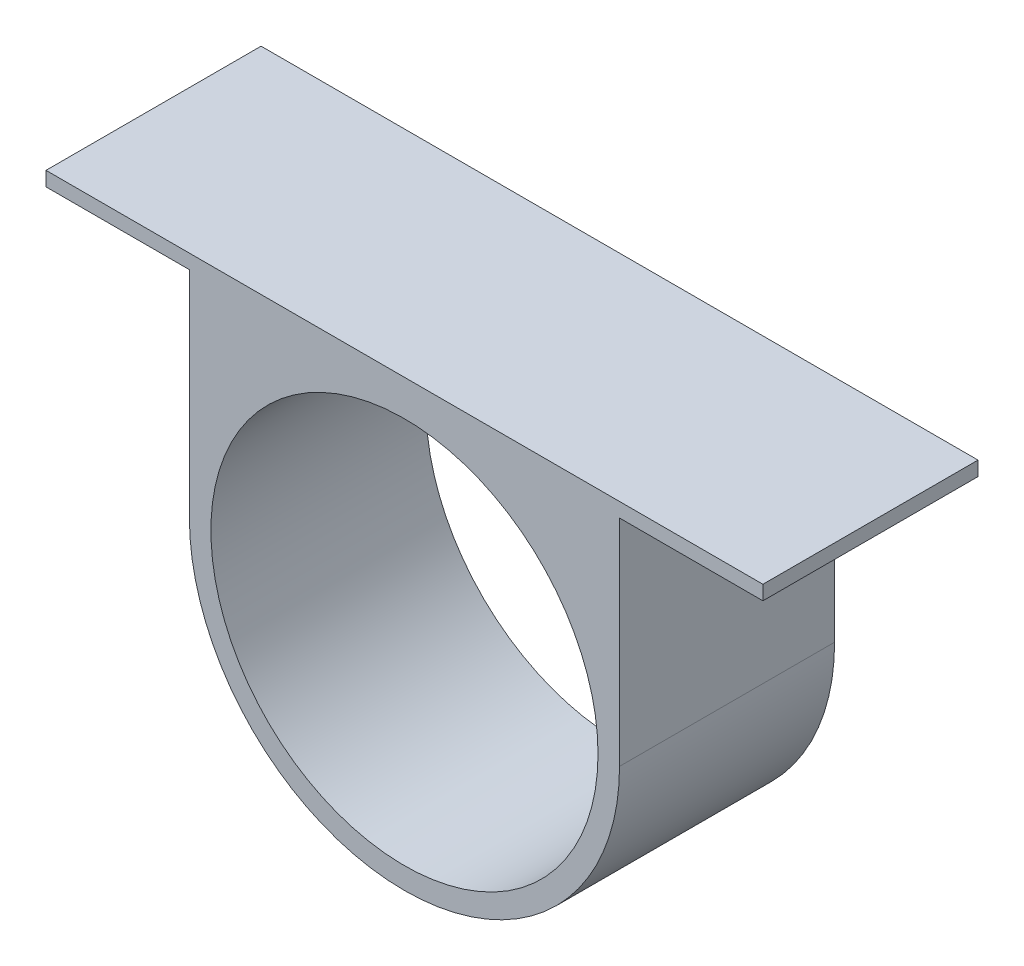
SolidWorks part; units mm, degrees
ref_plane "Front Plane" through (0, 0, 0) normal (0, 0, 1) x (1, 0, 0)
ref_plane "Top Plane" through (0, 0, 0) normal (0, 1, 0) x (1, 0, 0)
ref_plane "Right Plane" through (0, 0, 0) normal (1, 0, 0) x (0, 0, -1)
sketch "Sketch1" plane through (0, 0, 0) normal (0, 0, 1) x (1, 0, 0)
  line L0 (-15, 0) -> (-15, 15)
  line L1 (-15, 15) -> (-25, 15)
  line L2 (-25, 15) -> (-25, 16)
  line L3 (-25, 16) -> (25, 16)
  line L4 (0, 68.2101) -> (0, -66.7965) construction
  line L5 (25, 15) -> (25, 16)
  line L6 (15, 15) -> (25, 15)
  line L7 (15, 0) -> (15, 15)
  arc A0 (-15, 0) -> (15, 0) centre (0, 0) ccw
  circle A1 centre (0, 0) radius 13.5
  point P12 (0, 16)
  dimension "D1" = 27
  dimension "D2" = 30
  dimension "D3" = 15
  dimension "D4" = 1
  dimension "D5" = 10
extrude "Boss-Extrude1" add sketch "Sketch1" along normal blind 15
